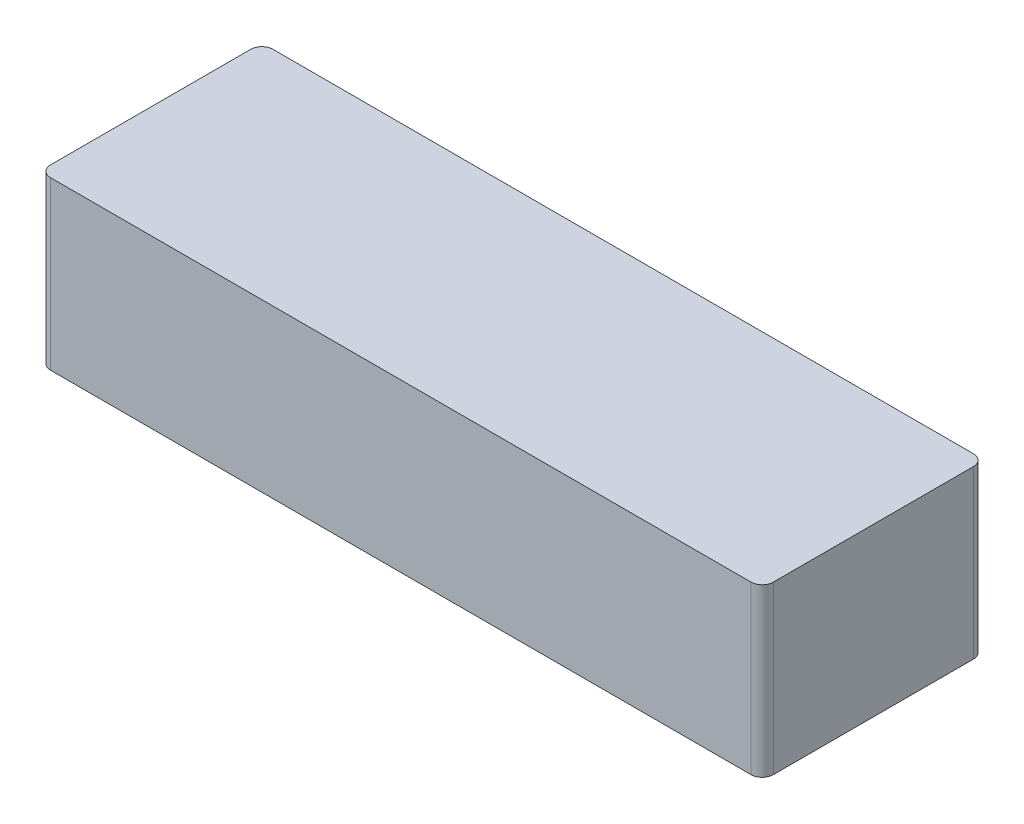
SolidWorks part; units mm, degrees
ref_plane "前视基准面" through (0, 0, 0) normal (0, 0, 1) x (1, 0, 0)
ref_plane "上视基准面" through (0, 0, 0) normal (0, 1, 0) x (1, 0, 0)
ref_plane "右视基准面" through (0, 0, 0) normal (1, 0, 0) x (0, 0, -1)
sketch "草图1" plane through (0, 0, 0) normal (0, 0, 1) x (1, 0, 0)
  line L1 (-65, -15) -> (65, -15)
  line L2 (-65, -15) -> (-65, 15)
  line L3 (-65, 15) -> (65, 15)
  line L4 (65, -15) -> (65, 15)
  line L5 (-65, -15) -> (65, 15) construction
  line L6 (-65, 15) -> (65, -15) construction
  point P0 (0, 0)
  dimension "D1" = 130
  dimension "D2" = 30
extrude "凸台-拉伸1" add sketch "草图1" along normal blind 40
fillet "圆角1" radius 2 4 edges at (65, 0, 0) (-65, 0, 0) (-65, 0, 40) (65, 0, 40)
